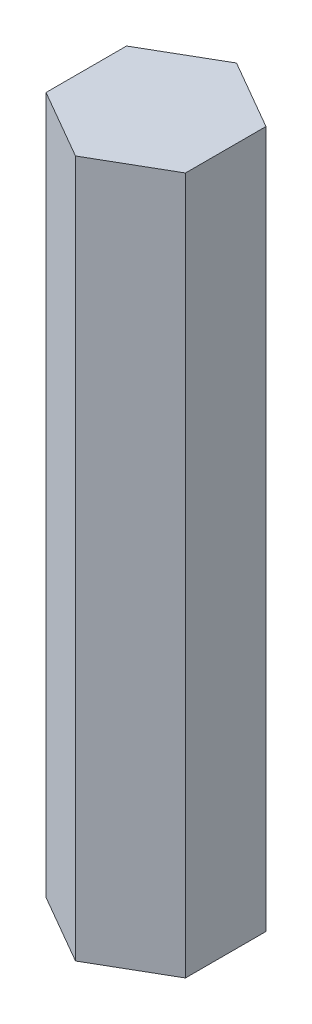
SolidWorks part; units mm, degrees
material "1060 Alloy"
ref_plane "Front" through (0, 0, 0) normal (0, 0, 1) x (1, 0, 0)
ref_plane "Top" through (0, 0, 0) normal (0, 1, 0) x (1, 0, 0)
ref_plane "Right" through (0, 0, 0) normal (1, 0, 0) x (0, 0, -1)
sketch "Sketch1" plane through (0, 0, 0) normal (0, 1, 0) x (1, 0, 0)
  line L1 (2.5, -1.4434) -> (2.5, 1.4434)
  line L2 (2.5, 1.4434) -> (0, 2.8868)
  line L3 (0, 2.8868) -> (-2.5, 1.4434)
  line L4 (-2.5, 1.4434) -> (-2.5, -1.4434)
  line L5 (-2.5, -1.4434) -> (0, -2.8868)
  line L6 (0, -2.8868) -> (2.5, -1.4434)
  circle A0 centre (0, 0) radius 2.5 construction
  dimension "D1" = 5
extrude "Boss-Extrude1" add sketch "Sketch1" along normal blind 25
